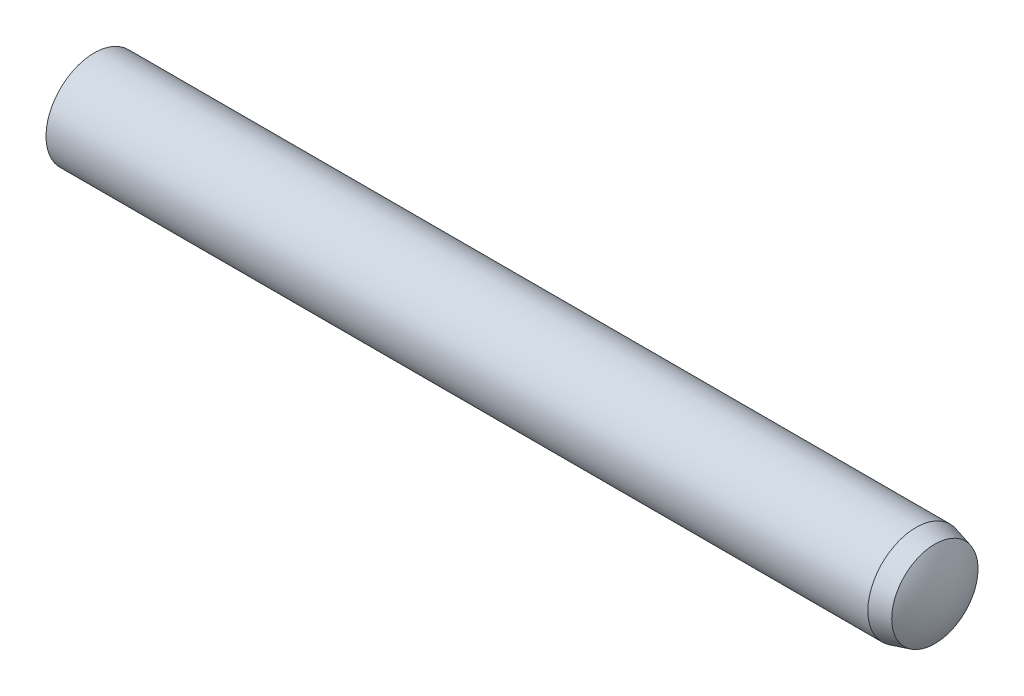
SolidWorks part; units mm, degrees
material "AISI 1015 Steel, Cold Drawn (SS)"
ref_plane "Front Plane" through (0, 0, 0) normal (0, 0, 1) x (1, 0, 0)
ref_plane "Top Plane" through (0, 0, 0) normal (0, 1, 0) x (1, 0, 0)
ref_plane "Right Plane" through (0, 0, 0) normal (1, 0, 0) x (0, 0, -1)
sketch "Sketch1" plane through (0, 0, 0) normal (0, 0, 1) x (1, 0, 0)
  line L0 (-9, 0) -> (9, 0) construction
  line L1 (9, 1) -> (9, -1) construction
  line L2 (-9, 1) -> (-9, -1) construction
  line L3 (8.35, 1) -> (8.35, -1) construction
  line L4 (-8.7, 1) -> (-8.7, -1) construction
  line L5 (-9, 0) -> (-8.7, 0) construction
  line L6 (9, 0) -> (8.35, 0) construction
  line L7 (8.74, 1) -> (8.74, -1) construction
  dimension "D1" = 0.65
  dimension "Dia" = 2
  dimension "D2" = 0.3
  dimension "Length" = 18
  dimension "D3" = 0.39
sketch "Sketch2" plane through (0, 0, 0) normal (1, 0, 0) x (0, 0, -1)
  circle A0 centre (0, 0) radius 1
extrude "Extrude1" add sketch "Sketch2" against normal up to vertex (9 mm away) and the other way up to vertex (9 mm away) up to point (-9, 0, 0) other way up to point (9, 0, 0)
sketch "Sketch5" plane through (0, 0, 0) normal (0, 0, 1) x (1, 0, 0)
  line L0 (8.35, 1) -> (8.35, 1.5)
  line L1 (8.35, 1.5) -> (9.5, 1.5)
  line L2 (9.5, 1.5) -> (9.5, 0)
  line L3 (9, 0) -> (9.5, 0)
  line L5 (-8.7, 1) -> (-8.7, 1.5)
  line L6 (-8.7, 1.5) -> (-9.5, 1.5)
  line L7 (-9.5, 1.5) -> (-9.5, 0)
  line L8 (8.35, 1) -> (8.74, 0.8955)
  line L10 (-9, 0) -> (-9.5, 0)
  line L11 (-9, 1) -> (-9, -1) construction
  line L13 (8.35, 1) -> (8.35, -1) construction
  line L15 (-9, 0) -> (9, 0) construction
  line L16 (8.74, 1) -> (8.74, -1) construction
  line L17 (9, 1) -> (9, -1) construction
  arc A0 (8.74, 0.8955) -> (9, 0) centre (7.3278, 0) cw
  arc A1 (-8.7, 1) -> (-9, 0) centre (-7.1833, 0) ccw
  dimension "D1" = 15
  dimension "D2" = 0.5
revolve "Cut-Revolve1" cut sketch "Sketch5" angle 360 about L0
equation "\"D1@Sketch1\" = \"Dia@Sketch1\"*.325"
equation "\"D2@Sketch1\" = \"Dia@Sketch1\"*.15"
equation "\"D3@Sketch1\" = \"D1@Sketch1\"*.6"
